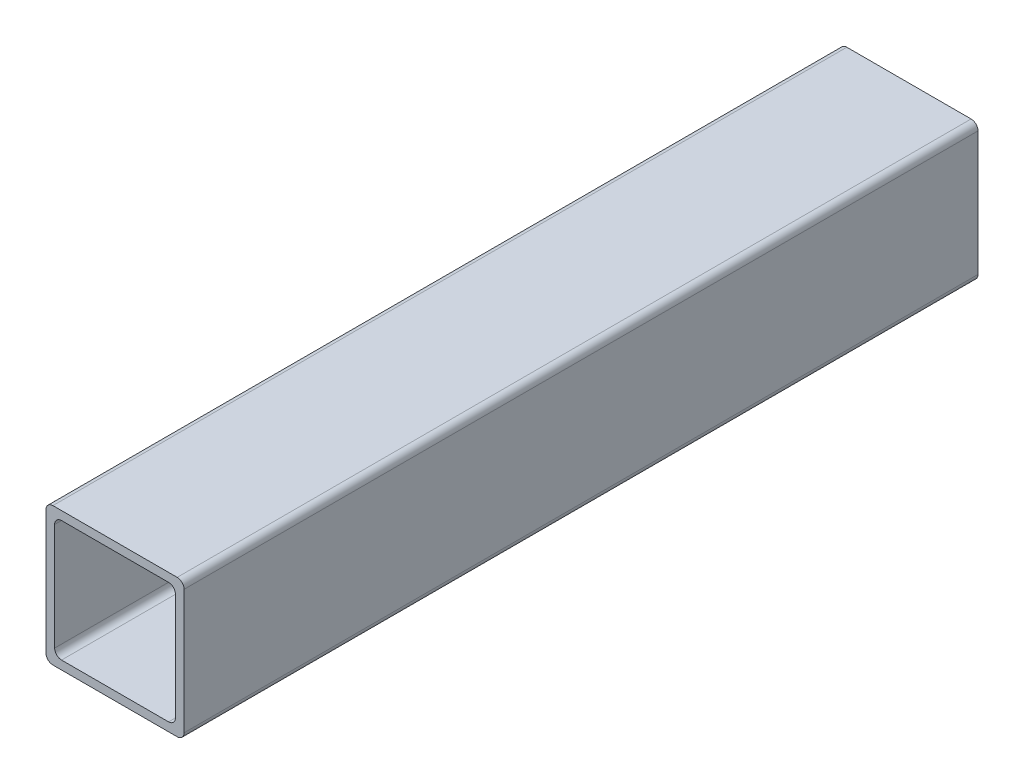
SolidWorks part; units mm, degrees
ref_plane "Front Plane" through (0, 0, 0) normal (0, 0, 1) x (1, 0, 0)
ref_plane "Top Plane" through (0, 0, 0) normal (0, 1, 0) x (1, 0, 0)
ref_plane "Right Plane" through (0, 0, 0) normal (1, 0, 0) x (0, 0, -1)
sketch "Sketch1" plane through (0, 0, 0) normal (0, 0, 1) x (1, 0, 0)
  line L0 (-19.685, 22.225) -> (19.685, 22.225)
  line L1 (-22.86, -25.4) -> (22.86, -25.4)
  line L2 (-25.4, -22.86) -> (-25.4, 22.86)
  line L3 (-22.86, 25.4) -> (22.86, 25.4)
  line L4 (25.4, -22.86) -> (25.4, 22.86)
  line L5 (-25.4, -25.4) -> (25.4, 25.4) construction
  line L6 (-25.4, 25.4) -> (25.4, -25.4) construction
  line L7 (22.225, -19.685) -> (22.225, 19.685)
  line L8 (-19.685, -22.225) -> (19.685, -22.225)
  line L9 (-22.225, -19.685) -> (-22.225, 19.685)
  line L10 (-22.225, -22.225) -> (22.225, -22.225) construction
  line L11 (-22.225, -22.225) -> (-22.225, 22.225) construction
  line L12 (-25.4, -25.4) -> (25.4, -25.4) construction
  line L13 (-25.4, -25.4) -> (-25.4, 25.4) construction
  line L14 (25.4, -25.4) -> (25.4, 25.4) construction
  line L15 (22.225, -22.225) -> (22.225, 22.225) construction
  line L16 (-22.225, 22.225) -> (22.225, 22.225) construction
  line L17 (-25.4, 25.4) -> (25.4, 25.4) construction
  arc A0 (-19.685, -22.225) -> (-22.225, -19.685) centre (-19.685, -19.685) cw
  arc A1 (-22.86, -25.4) -> (-25.4, -22.86) centre (-22.86, -22.86) cw
  arc A2 (22.86, -25.4) -> (25.4, -22.86) centre (22.86, -22.86) ccw
  arc A3 (22.225, -19.685) -> (19.685, -22.225) centre (19.685, -19.685) cw
  arc A4 (19.685, 22.225) -> (22.225, 19.685) centre (19.685, 19.685) cw
  arc A5 (22.86, 25.4) -> (25.4, 22.86) centre (22.86, 22.86) cw
  arc A6 (-25.4, 22.86) -> (-22.86, 25.4) centre (-22.86, 22.86) cw
  arc A7 (-19.685, 22.225) -> (-22.225, 19.685) centre (-19.685, 19.685) ccw
  point P0 (0, 0)
  dimension "D4" = 2.54
  dimension "D1" = 50.8
  dimension "D2" = 50.8
  dimension "D3" = 3.175
extrude "Boss-Extrude1" add sketch "Sketch1" along normal mid plane 292.1
